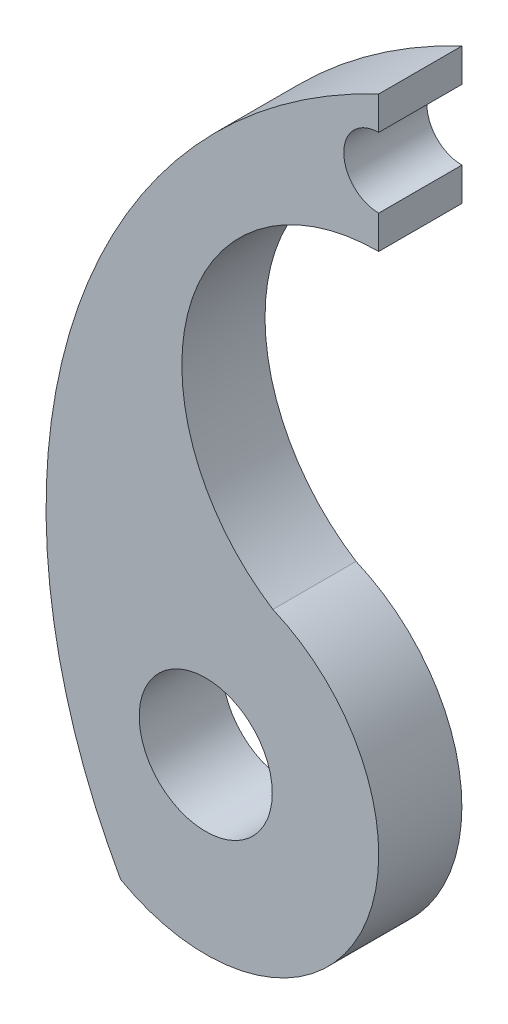
SolidWorks part; units mm, degrees
ref_plane "Front Plane" through (0, 0, 0) normal (0, 0, 1) x (1, 0, 0)
ref_plane "Top Plane" through (0, 0, 0) normal (0, 1, 0) x (1, 0, 0)
ref_plane "Right Plane" through (0, 0, 0) normal (1, 0, 0) x (0, 0, -1)
sketch "Sketch1" plane through (0, 0, 0) normal (0, 0, 1) x (1, 0, 0)
  line L0 (-1000, 0) -> (0, 0) construction
  line L1 (-1000, 31.75) -> (60.9049, 31.75) construction
  line L2 (0, 0) -> (0, 31.75) construction
  line L3 (-12.7, 11.7153) -> (-12.7, 31.75) construction
  line L5 (0, 27.813) -> (0, 26.543)
  line L6 (0, 30.48) -> (0, 31.75)
  line L7 (-1000, 0) -> (60.9049, 0) construction
  arc A0 (0, 30.48) -> (0, 27.813) centre (0, 29.1465) ccw
  arc A1 (-9.8559, 0.8561) -> (-4.0404, 12.6901) centre (-6.604, 6.604) ccw
  circle A2 centre (-6.604, 6.604) radius 2.54
  arc A3 (0, 31.75) -> (-9.8559, 0.8561) centre (9.4528, 11.7153) ccw
  arc A5 (0, 26.543) -> (-4.0404, 12.6901) centre (0, 19.0273) ccw
  dimension "D3" = 2.667
  dimension "D4" = 1.27
  dimension "D6" = 6.604
  dimension "D5" = 5.08
  dimension "D2" = 12.7
  dimension "D1" = 31.75
extrude "Boss-Extrude1" add sketch "Sketch1" along normal blind 3.175
